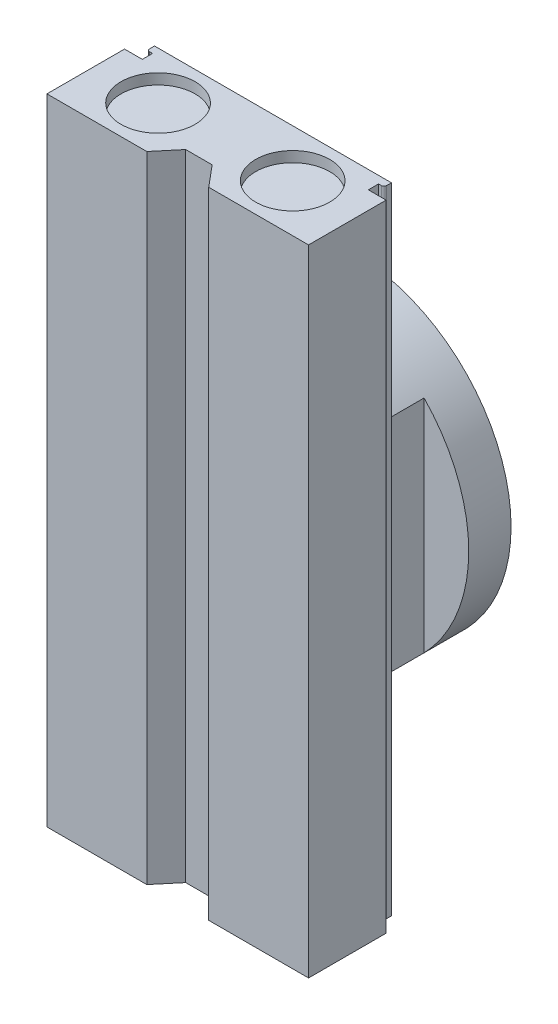
SolidWorks part; units mm, degrees
ref_plane "Plan de face" through (0, 0, 0) normal (0, 0, 1) x (1, 0, 0)
ref_plane "Plan de dessus" through (0, 0, 0) normal (0, 1, 0) x (1, 0, 0)
ref_plane "Plan de droite" through (0, 0, 0) normal (1, 0, 0) x (0, 0, -1)
sketch "Esquisse1" plane through (0, 0, 0) normal (0, 0, 1) x (1, 0, 0)
  circle A0 centre (0, 0) radius 30
  dimension "D1" = 60
extrude "Boss.-Extru.1" add sketch "Esquisse1" along normal blind 15
sketch "Esquisse2" plane through (0, 0, 15) normal (0, 0, 1) x (1, 0, 0)
  line L0 (0, 0) -> (0, 13.9711) construction
  line L1 (21.56, 26.1841) -> (30.9008, 26.1841)
  line L2 (21.56, 26.1841) -> (21.56, -26.8777)
  line L3 (21.56, -26.8777) -> (30.9008, -26.8777)
  line L4 (30.9008, 26.1841) -> (30.9008, -26.8777)
  line L5 (-30.9008, 26.1841) -> (-30.9008, -26.8777)
  line L6 (-21.56, -26.8777) -> (-30.9008, -26.8777)
  line L7 (-21.56, 26.1841) -> (-21.56, -26.8777)
  line L8 (-21.56, 26.1841) -> (-30.9008, 26.1841)
extrude "Enlèv. mat.-Extru.1" cut sketch "Esquisse2" against normal blind 7
sketch "Esquisse3" plane through (0, 0, 15) normal (0, 0, 1) x (1, 0, 0)
  line L1 (24.7249, -60) -> (-24.7249, -60)
  line L2 (24.7249, -60) -> (24.7249, 60)
  line L3 (24.7249, 60) -> (-24.7249, 60)
  line L4 (-24.7249, -60) -> (-24.7249, 60)
  line L5 (24.7249, -60) -> (-24.7249, 60) construction
  line L6 (24.7249, 60) -> (-24.7249, -60) construction
  point P0 (0, 0)
  dimension "D1" = 120
extrude "Boss.-Extru.2" add sketch "Esquisse3" along normal blind 18
sketch "Esquisse4" plane through (0, -60, 0) normal (0, -1, 0) x (1, 0, 0)
  line L0 (-24.7249, 33) -> (-24.7249, 15) construction
  line L1 (24.7249, 33) -> (24.7249, 15) construction
  circle A0 centre (12.7249, 24) radius 7
  circle A1 centre (-12.7249, 24) radius 7
  dimension "D1" = 14
  dimension "D2" = 14
  dimension "D3" = 12
  dimension "D4" = 12
extrude "Enlèv. mat.-Extru.2" cut sketch "Esquisse4" against normal blind 2
mirror "Symétrie1" about plane through (0, 0, 0) normal (0, 1, 0) of "Enlèv. mat.-Extru.2"
sketch "Esquisse5" plane through (0, -60, 0) normal (0, -1, 0) x (1, 0, 0)
  line L0 (24.7249, 18.3358) -> (21.3562, 18.3358)
  line L1 (24.7249, 33) -> (24.7249, 15) construction
  line L2 (21.3562, 18.3358) -> (21.3562, 16.4104)
  line L3 (21.3562, 16.4104) -> (21.8896, 16.4104)
  line L4 (22.3896, 15.9104) -> (22.3896, 15)
  line L5 (-24.7249, 15) -> (24.7249, 15) construction
  line L6 (0, 33) -> (0, 39.2502) construction
  line L7 (-24.7249, 33) -> (24.7249, 33) construction
  line L8 (-22.3896, 15.9104) -> (-22.3896, 15)
  line L9 (-21.3562, 16.4104) -> (-21.8896, 16.4104)
  line L10 (-21.3562, 18.3358) -> (-21.3562, 16.4104)
  line L11 (-24.7249, 18.3358) -> (-21.3562, 18.3358)
  line L12 (24.7249, 18.3358) -> (26.0271, 18.3358)
  line L13 (26.0271, 18.3358) -> (26.0271, 13.1397)
  line L14 (26.0271, 13.1397) -> (22.7007, 13.1397)
  line L15 (22.7007, 13.1397) -> (22.3896, 15)
  line L17 (-24.7249, 18.3358) -> (-25.8429, 18.3358)
  line L18 (-25.8429, 18.3358) -> (-25.5458, 13.7575)
  line L19 (-25.5458, 13.7575) -> (-22.3896, 13.7575)
  line L20 (-22.3896, 13.7575) -> (-22.3896, 15)
  arc A0 (22.3896, 15.9104) -> (21.8896, 16.4104) centre (21.8896, 15.9104) ccw
  arc A1 (-22.3896, 15.9104) -> (-21.8896, 16.4104) centre (-21.8896, 15.9104) cw
  dimension "D1" = 0.5
extrude "Enlèv. mat.-Extru.3" cut sketch "Esquisse5" against normal through all
sketch "Esquisse6" plane through (0, 0, 0) normal (0, 0, -1) x (-1, 0, 0)
  circle A0 centre (0, 0) radius 10
  dimension "D1" = 20
extrude "Boss.-Extru.3" add sketch "Esquisse6" along normal blind 10
sketch "Esquisse7" plane through (0, 0, 33) normal (0, 0, 1) x (1, 0, 0)
  line L0 (24.7249, 60) -> (-24.7249, 60) construction
  line L1 (2.5, -60) -> (-2.5, -60)
  line L2 (2.5, -60) -> (2.5, 60)
  line L3 (2.5, 60) -> (-2.5, 60)
  line L4 (-2.5, -60) -> (-2.5, 60)
  line L5 (2.5, -60) -> (-2.5, 60) construction
  line L6 (2.5, 60) -> (-2.5, -60) construction
  point P0 (0, 0)
  dimension "D1" = 5
extrude "Enlèv. mat.-Extru.4" cut sketch "Esquisse7" against normal blind 4
draft "Dépouille1" type of draft neutral plane draft angle 40 faces to draft 2 face at (-2.5, 0, 31) face at (2.5, 0, 31) neutral plane through (-2.5, 60, 29) neutral plane normal (0, 0, 1) parameters "D1"=40
